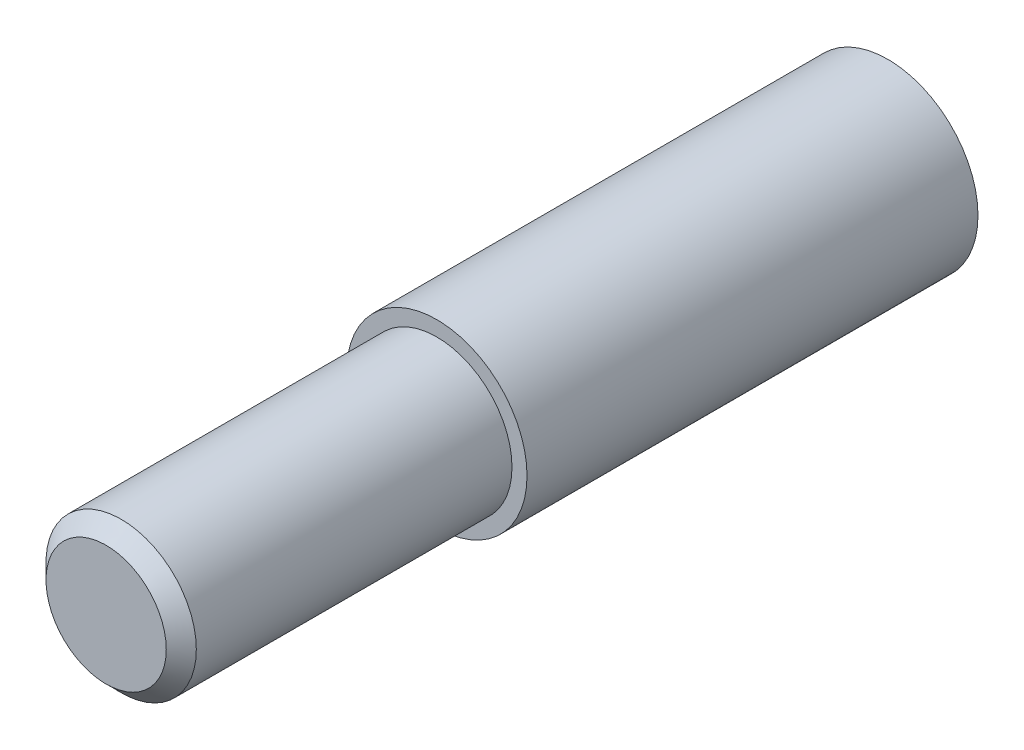
SolidWorks part; units mm, degrees
ref_plane "Alzado" through (0, 0, 0) normal (0, 0, 1) x (1, 0, 0)
ref_plane "Planta" through (0, 0, 0) normal (0, 1, 0) x (1, 0, 0)
ref_plane "Vista lateral" through (0, 0, 0) normal (1, 0, 0) x (0, 0, -1)
sketch "Croquis1" plane through (0, 0, 0) normal (0, 0, 1) x (1, 0, 0)
  circle A0 centre (0, 0) radius 6
  dimension "D1" = 12
extrude "Saliente-Extruir1" add sketch "Croquis1" along normal blind 30
sketch "Croquis2" plane through (0, 0, 30) normal (0, 0, 1) x (1, 0, 0)
  circle A0 centre (0, 0) radius 5
  dimension "D1" = 10
extrude "Saliente-Extruir2" add sketch "Croquis2" along normal blind 22
chamfer "Chaflán1" distance 1 angle 45 1 edges at (5, 0, 52)
